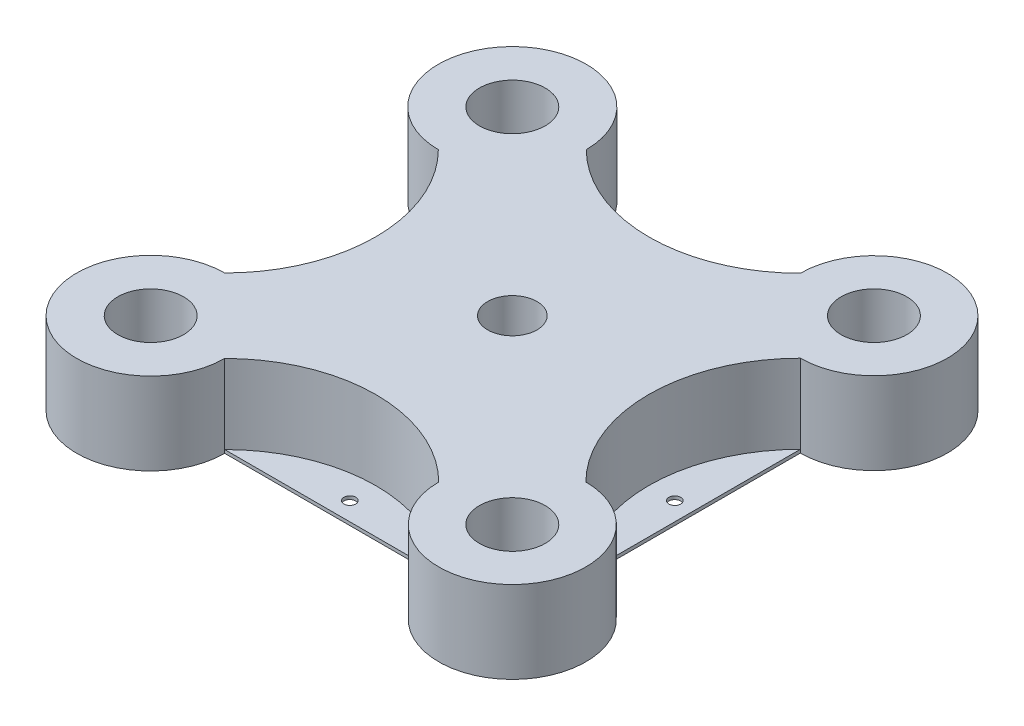
SolidWorks part; units mm, degrees
ref_plane "Front Plane" through (0, 0, 0) normal (0, 0, 1) x (1, 0, 0)
ref_plane "Top Plane" through (0, 0, 0) normal (0, 1, 0) x (1, 0, 0)
ref_plane "Right Plane" through (0, 0, 0) normal (1, 0, 0) x (0, 0, -1)
sketch "Çizim1" plane through (0, 0, 0) normal (0, 1, 0) x (1, 0, 0)
  line L0 (-550, 325) -> (-550, -324.873)
  line L1 (550, 326.2033) -> (550, -326.2033)
  line L2 (-324.873, -550) -> (326.2033, -550)
  line L3 (-325, 550) -> (326.2033, 550)
  circle A0 centre (0, 0) radius 75
  circle A8 centre (-550, 550) radius 100
  circle A9 centre (550, 550) radius 100
  circle A10 centre (550, -550) radius 100
  circle A11 centre (-550, -550) radius 100
  circle A12 centre (-550, 550) radius 225
  circle A13 centre (550, 550) radius 223.7967
  circle A14 centre (550, -550) radius 223.7967
  circle A15 centre (-550, -550) radius 225.127
  point P16 (900, 900)
  point P19 (900, -900)
  point P22 (-900, -900)
  point P25 (-900, 900)
  dimension "D1" = 550
  dimension "D3" = 150
  dimension "D16" = 450
  dimension "D2" = 550
  dimension "D6" = 1100
extrude "Yükseklik-Ekstrüzyon3" add sketch "Çizim1" along normal blind 250 contours A15 L2 A14 L1 A13 L3 A12 L0 | A12 A8 | A13 A9 | A14 A10 | A11
sketch "Çizim2" plane through (0, 250, 0) normal (0, 1, 0) x (1, 0, 0)
  line L0 (-325, 550) -> (326.2033, 550) construction
  line L1 (-550, 325) -> (-550, -324.873)
  line L2 (-324.873, -550) -> (326.2033, -550)
  line L3 (-325, 550) -> (326.2033, 550)
  line L4 (550, 326.2033) -> (550, -326.2033)
  arc A0 (-550, 325) -> (-550, -324.873) centre (-874.9365, 0.0635) cw
  arc A1 (550, 326.2033) -> (550, -326.2033) centre (876.2033, 0) ccw
  arc A2 (-325, 550) -> (326.2033, 550) centre (0.6017, 875.6017) ccw
  arc A3 (-325, 550) -> (-550, 325) centre (-550, 550) ccw construction
  arc A4 (-324.873, -550) -> (326.2033, -550) centre (0.6652, -875.5381) cw
extrude "Kes-Ekstrüzyon2" cut sketch "Çizim2" against normal blind 240
sketch "Çizim4" plane through (0, 10, 0) normal (0, 1, 0) x (1, 0, 0)
  circle A0 centre (-494.2847, 0.0635) radius 18
extrude "Kes-Ekstrüzyon3" cut sketch "Çizim4" against normal blind 240
pattern_circular "Dairesel Kaplama1" count 4 every 90 about axis through (0, 0, 0) along (0, 1, 0) of "Kes-Ekstrüzyon3"
